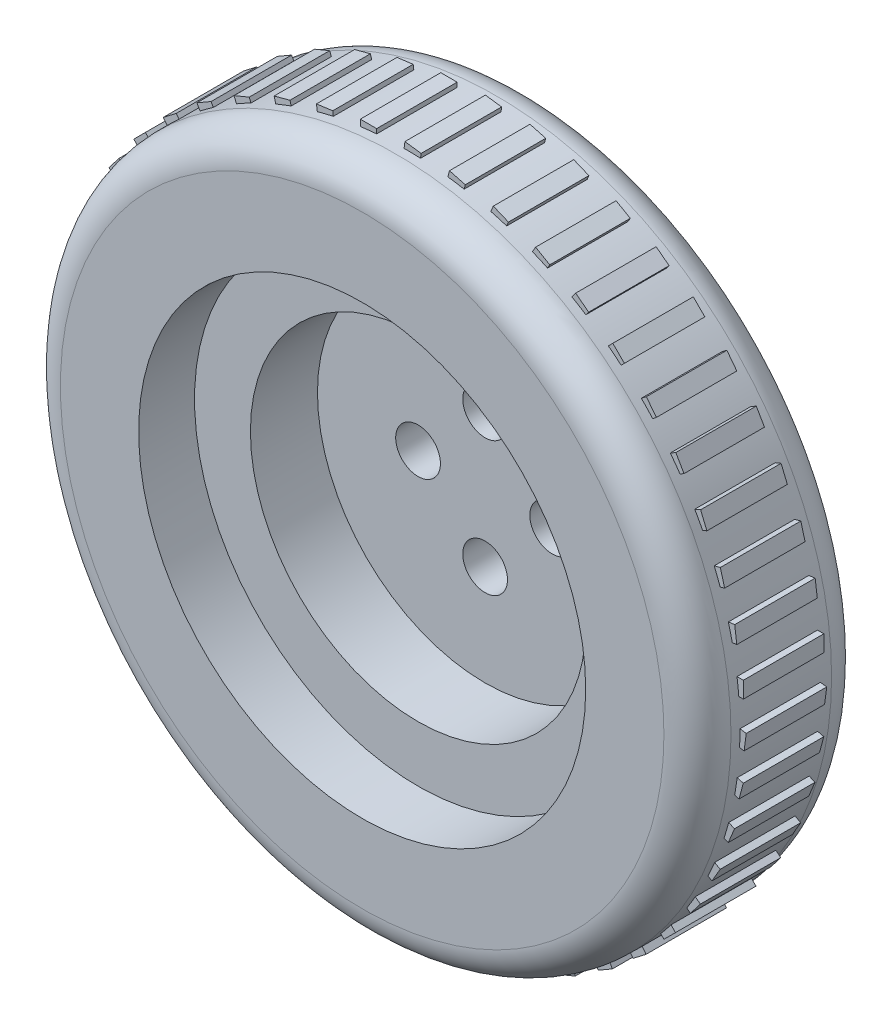
SolidWorks part; units mm, degrees
ref_plane "前基準面" through (0, 0, 0) normal (0, 0, 1) x (1, 0, 0)
ref_plane "上基準面" through (0, 0, 0) normal (0, 1, 0) x (1, 0, 0)
ref_plane "右基準面" through (0, 0, 0) normal (1, 0, 0) x (0, 0, -1)
sketch "草圖1" plane through (0, 0, 0) normal (0, 0, 1) x (1, 0, 0)
  circle A0 centre (0, 0) radius 30
  dimension "D1" = 60
extrude "填料-伸長1" add sketch "草圖1" along normal blind 15
sketch "草圖2" plane through (0, 0, 15) normal (0, 0, 1) x (1, 0, 0)
  circle A0 centre (0, 0) radius 20
  dimension "D1" = 40
extrude "除料-伸長1" cut sketch "草圖2" against normal blind 5
sketch "草圖3" plane through (0, 0, 10) normal (0, 0, 1) x (1, 0, 0)
  circle A0 centre (6, 0) radius 2
  circle A1 centre (-6, 0) radius 2
  circle A2 centre (0, 6) radius 2
  circle A3 centre (0, -6) radius 2
  dimension "D1" = 4
  dimension "D2" = 6
  dimension "D6" = 4
  dimension "D7" = 4
  dimension "D8" = 4
  dimension "D3" = 6
  dimension "D4" = 6
  dimension "D5" = 6
extrude "除料-伸長2" cut sketch "草圖3" against normal through all
sketch "草圖5" plane through (0, 0, 10) normal (0, 0, 1) x (1, 0, 0)
  circle A0 centre (0, 0) radius 15
  dimension "D1" = 30
extrude "除料-伸長3" cut sketch "草圖5" against normal blind 6
fillet "圓角1" radius 3 2 edges at (30, 0, 0) (30, 0, 15)
sketch "草圖7" plane through (0, 0, 4) normal (0, 0, 1) x (1, 0, 0)
  line L1 (-3.967, 30.3059) -> (-2.5023, 30.3059)
  line L2 (-3.967, 30.3059) -> (-3.967, 29.1729)
  line L3 (-3.967, 29.1729) -> (-2.5023, 29.1729)
  line L4 (-2.5023, 30.3059) -> (-2.5023, 29.1729)
extrude "填料-伸長2" add sketch "草圖7" along normal blind 7.2
pattern_circular "環狀複製排列1" count 48 over 360 about axis through (0, 0, 0) along (0, 0, 1) of "填料-伸長2"
